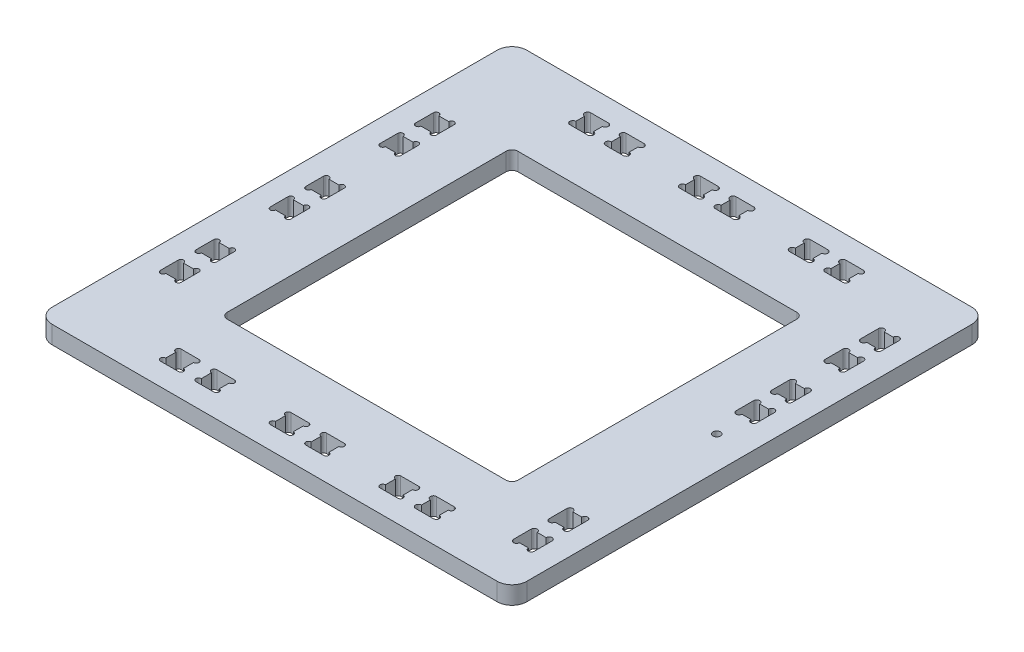
SolidWorks part; units mm, degrees
ref_plane "정면" through (0, 0, 0) normal (0, 0, 1) x (1, 0, 0)
ref_plane "윗면" through (0, 0, 0) normal (0, 1, 0) x (1, 0, 0)
ref_plane "우측면" through (0, 0, 0) normal (1, 0, 0) x (0, 0, -1)
sketch "스케치1" plane through (0, 0, 0) normal (0, 1, 0) x (1, 0, 0)
  line L1 (-80, -80) -> (80, -80)
  line L2 (-80, -80) -> (-80, 80)
  line L3 (-80, 80) -> (80, 80)
  line L4 (80, -80) -> (80, 80)
  line L5 (-80, -80) -> (80, 80) construction
  line L6 (-80, 80) -> (80, -80) construction
  line L7 (-49, -49) -> (49, -49)
  line L8 (-49, -49) -> (-49, 49)
  line L9 (-49, 49) -> (49, 49)
  line L10 (49, -49) -> (49, 49)
  line L11 (-49, -49) -> (49, 49) construction
  line L12 (-49, 49) -> (49, -49) construction
  point P0 (0, 0)
  point P6 (0, 0)
  dimension "D1" = 98
  dimension "D2" = 98
  dimension "D3" = 160
  dimension "D4" = 160
extrude "보스-돌출1" add sketch "스케치1" along normal blind 6
sketch "스케치2" plane through (0, 0, 0) normal (0, -1, 0) x (1, 0, 0)
  line L1 (-46, 72.5) -> (-40, 72.5)
  line L2 (-46, 72.5) -> (-46, 65.5)
  line L3 (-46, 65.5) -> (-40, 65.5)
  line L4 (-40, 72.5) -> (-40, 65.5)
  line L5 (-34, 72.5) -> (-28, 72.5)
  line L6 (-34, 72.5) -> (-34, 65.5)
  line L7 (-34, 65.5) -> (-28, 65.5)
  line L8 (-28, 72.5) -> (-28, 65.5)
  line L9 (-9, 72.5) -> (-3, 72.5)
  line L10 (-9, 72.5) -> (-9, 65.5)
  line L11 (-9, 65.5) -> (-3, 65.5)
  line L12 (-3, 72.5) -> (-3, 65.5)
  line L13 (3, 72.5) -> (9, 72.5)
  line L14 (3, 72.5) -> (3, 65.5)
  line L15 (3, 65.5) -> (9, 65.5)
  line L16 (9, 72.5) -> (9, 65.5)
  line L17 (28, 72.5) -> (34, 72.5)
  line L18 (28, 72.5) -> (28, 65.5)
  line L19 (28, 65.5) -> (34, 65.5)
  line L20 (34, 72.5) -> (34, 65.5)
  line L21 (40, 72.5) -> (46, 72.5)
  line L22 (40, 72.5) -> (40, 65.5)
  line L23 (40, 65.5) -> (46, 65.5)
  line L24 (46, 72.5) -> (46, 65.5)
  line L25 (65.5, 65) -> (72.5, 65)
  line L26 (65.5, 65) -> (65.5, 59)
  line L27 (65.5, 59) -> (72.5, 59)
  line L28 (72.5, 65) -> (72.5, 59)
  line L29 (65.5, 53) -> (72.5, 53)
  line L30 (65.5, 53) -> (65.5, 47)
  line L31 (65.5, 47) -> (72.5, 47)
  line L32 (72.5, 53) -> (72.5, 47)
  line L33 (65.5, -10) -> (72.5, -10)
  line L34 (65.5, -10) -> (65.5, -16)
  line L35 (65.5, -16) -> (72.5, -16)
  line L36 (72.5, -10) -> (72.5, -16)
  line L37 (65.5, -22) -> (72.5, -22)
  line L38 (65.5, -22) -> (65.5, -28)
  line L39 (65.5, -28) -> (72.5, -28)
  line L40 (72.5, -22) -> (72.5, -28)
  line L41 (65.5, -40) -> (72.5, -40)
  line L42 (65.5, -40) -> (65.5, -46)
  line L43 (65.5, -46) -> (72.5, -46)
  line L44 (72.5, -40) -> (72.5, -46)
  line L45 (65.5, -52) -> (72.5, -52)
  line L46 (65.5, -52) -> (65.5, -58)
  line L47 (65.5, -58) -> (72.5, -58)
  line L48 (72.5, -52) -> (72.5, -58)
  line L49 (3, -65.5) -> (9, -65.5)
  line L50 (3, -65.5) -> (3, -72.5)
  line L51 (3, -72.5) -> (9, -72.5)
  line L52 (9, -65.5) -> (9, -72.5)
  line L53 (-3, -65.5) -> (-9, -65.5)
  line L54 (-3, -65.5) -> (-3, -72.5)
  line L55 (-3, -72.5) -> (-9, -72.5)
  line L56 (-9, -65.5) -> (-9, -72.5)
  line L57 (-28, -65.5) -> (-34, -65.5)
  line L58 (-28, -65.5) -> (-28, -72.5)
  line L59 (-28, -72.5) -> (-34, -72.5)
  line L60 (-34, -65.5) -> (-34, -72.5)
  line L61 (-40, -65.5) -> (-46, -65.5)
  line L62 (-40, -65.5) -> (-40, -72.5)
  line L63 (-40, -72.5) -> (-46, -72.5)
  line L64 (-46, -65.5) -> (-46, -72.5)
  line L65 (-65.5, -40) -> (-72.5, -40)
  line L66 (-65.5, -40) -> (-65.5, -46)
  line L67 (-65.5, -46) -> (-72.5, -46)
  line L68 (-72.5, -40) -> (-72.5, -46)
  line L69 (-72.5, -34) -> (-65.5, -34)
  line L70 (-72.5, -34) -> (-72.5, -28)
  line L71 (-72.5, -28) -> (-65.5, -28)
  line L72 (-65.5, -34) -> (-65.5, -28)
  line L73 (-72.5, -9) -> (-65.5, -9)
  line L74 (-72.5, -9) -> (-72.5, -3)
  line L75 (-72.5, -3) -> (-65.5, -3)
  line L76 (-65.5, -9) -> (-65.5, -3)
  line L77 (-72.5, 3) -> (-65.5, 3)
  line L78 (-72.5, 3) -> (-72.5, 9)
  line L79 (-72.5, 9) -> (-65.5, 9)
  line L80 (-65.5, 3) -> (-65.5, 9)
  line L81 (-72.5, 28) -> (-65.5, 28)
  line L82 (-72.5, 28) -> (-72.5, 34)
  line L83 (-72.5, 34) -> (-65.5, 34)
  line L84 (-65.5, 28) -> (-65.5, 34)
  line L85 (-72.5, 40) -> (-65.5, 40)
  line L86 (-72.5, 40) -> (-72.5, 46)
  line L87 (-72.5, 46) -> (-65.5, 46)
  line L88 (-65.5, 40) -> (-65.5, 46)
  line L89 (28, -65.5) -> (34, -65.5)
  line L90 (28, -65.5) -> (28, -72.5)
  line L91 (28, -72.5) -> (34, -72.5)
  line L92 (34, -65.5) -> (34, -72.5)
  line L93 (40, -65.5) -> (46, -65.5)
  line L94 (40, -65.5) -> (40, -72.5)
  line L95 (40, -72.5) -> (46, -72.5)
  line L96 (46, -65.5) -> (46, -72.5)
extrude "컷-돌출1" cut sketch "스케치2" against normal blind 10
fillet "필렛1" radius 5 4 edges at (-80, 3, -80) (80, 3, -80) (80, 3, 80) (-80, 3, 80)
fillet "필렛2" radius 2 4 edges at (49, 3, 49) (49, 3, -49) (-49, 3, -49) (-49, 3, 49)
sketch "스케치3" plane through (0, 6, 0) normal (0, 1, 0) x (1, 0, 0)
  line L0 (80, 10) -> (73.6162, 3.6162)
  line L1 (80, -75) -> (80, 75) construction
  line L2 (73.6162, 3.6162) -> (73.6162, -35.3838)
  line L3 (73.6162, -35.3838) -> (80, -41.7676)
  line L4 (80, 10) -> (80, -41.7676)
  line L6 (72.5, 10) -> (80, 10) construction
  dimension "D1" = 45
  dimension "D2" = 45
  dimension "D3" = 39
extrude "컷-돌출2" [suppressed] cut sketch "스케치3" against normal blind 10
sketch "스케치4" plane through (0, 6, 0) normal (0, 1, 0) x (1, 0, 0)
  line L0 (49, 0) -> (84.68, 0) construction
  line L1 (49, -47) -> (49, 47) construction
  circle A0 centre (69, 0) radius 1.25
  dimension "D1" = 2.5
  dimension "D2" = 20
extrude "컷-돌출3" cut sketch "스케치4" against normal through all
sketch "스케치5" plane through (0, 6, 0) normal (0, 1, 0) x (1, 0, 0)
  line L0 (46, 72.5) -> (46, 65.5) construction
  line L1 (40, 65.5) -> (40, 72.5) construction
  line L2 (34, 72.5) -> (34, 65.5) construction
  line L3 (28, 65.5) -> (28, 72.5) construction
  line L4 (9, 72.5) -> (9, 65.5) construction
  line L5 (3, 65.5) -> (3, 72.5) construction
  line L6 (-3, 72.5) -> (-3, 65.5) construction
  line L7 (-9, 65.5) -> (-9, 72.5) construction
  line L8 (-40, 72.5) -> (-40, 65.5) construction
  line L9 (-46, 65.5) -> (-46, 72.5) construction
  line L10 (-34, 65.5) -> (-34, 72.5) construction
  line L11 (-28, 72.5) -> (-28, 65.5) construction
  line L12 (65.5, 58) -> (72.5, 58) construction
  line L13 (72.5, 52) -> (65.5, 52) construction
  line L14 (72.5, 40) -> (65.5, 40) construction
  line L15 (65.5, 46) -> (72.5, 46) construction
  line L16 (65.5, 28) -> (72.5, 28) construction
  line L17 (72.5, 22) -> (65.5, 22) construction
  line L18 (65.5, 16) -> (72.5, 16) construction
  line L19 (72.5, 10) -> (65.5, 10) construction
  line L20 (65.5, -47) -> (72.5, -47) construction
  line L21 (72.5, -53) -> (65.5, -53) construction
  line L22 (65.5, -59) -> (72.5, -59) construction
  line L23 (72.5, -65) -> (65.5, -65) construction
  line L24 (46, -65.5) -> (46, -72.5) construction
  line L25 (40, -72.5) -> (40, -65.5) construction
  line L26 (34, -65.5) -> (34, -72.5) construction
  line L27 (28, -72.5) -> (28, -65.5) construction
  line L28 (3, -72.5) -> (3, -65.5) construction
  line L29 (9, -65.5) -> (9, -72.5) construction
  line L30 (-3, -65.5) -> (-3, -72.5) construction
  line L31 (-9, -72.5) -> (-9, -65.5) construction
  line L32 (-34, -72.5) -> (-34, -65.5) construction
  line L33 (-28, -65.5) -> (-28, -72.5) construction
  line L34 (-40, -65.5) -> (-40, -72.5) construction
  line L35 (-46, -72.5) -> (-46, -65.5) construction
  line L36 (-72.5, 46) -> (-65.5, 46) construction
  line L37 (-65.5, 40) -> (-72.5, 40) construction
  line L38 (-72.5, 34) -> (-65.5, 34) construction
  line L39 (-65.5, 28) -> (-72.5, 28) construction
  line L40 (-72.5, 9) -> (-65.5, 9) construction
  line L41 (-65.5, 3) -> (-72.5, 3) construction
  line L42 (-72.5, -3) -> (-65.5, -3) construction
  line L43 (-65.5, -9) -> (-72.5, -9) construction
  line L44 (-72.5, -28) -> (-65.5, -28) construction
  line L45 (-65.5, -34) -> (-72.5, -34) construction
  line L46 (-72.5, -40) -> (-65.5, -40) construction
  line L47 (-65.5, -46) -> (-72.5, -46) construction
  circle A0 centre (28, -66.4077) radius 0.9077
  circle A1 centre (40, 71.5) radius 1
  circle A2 centre (40, 66.5) radius 1
  circle A3 centre (46, 66.5) radius 1
  circle A4 centre (34, 71.5) radius 1
  circle A5 centre (28, 71.5) radius 1
  circle A6 centre (28, 66.5) radius 1
  circle A7 centre (34, 66.5) radius 1
  circle A8 centre (9, 71.5) radius 1
  circle A9 centre (3, 71.5) radius 1
  circle A10 centre (3, 66.5) radius 1
  circle A11 centre (9, 66.5) radius 1
  circle A12 centre (-3, 71.5) radius 1
  circle A13 centre (-3, 66.5) radius 1
  circle A14 centre (-9, 66.5) radius 1
  circle A15 centre (-9, 71.5) radius 1
  circle A16 centre (-40, 71.5) radius 1
  circle A17 centre (-40, 66.5) radius 1
  circle A18 centre (-46, 66.5) radius 1
  circle A19 centre (-46, 71.5) radius 1
  circle A20 centre (-34, 71.5) radius 1
  circle A21 centre (-28, 71.5) radius 1
  circle A22 centre (-28, 66.5) radius 1
  circle A23 centre (-34, 66.5) radius 1
  circle A24 centre (71.5, 58) radius 1
  circle A25 centre (66.5, 58) radius 1
  circle A26 centre (66.5, 52) radius 1
  circle A27 centre (71.5, 52) radius 1
  circle A28 centre (66.5, 40) radius 1
  circle A29 centre (66.5, 46) radius 1
  circle A30 centre (71.5, 46) radius 1
  circle A31 centre (71.5, 40) radius 1
  circle A32 centre (66.5, 28) radius 1
  circle A33 centre (71.5, 28) radius 1
  circle A34 centre (71.5, 22) radius 1
  circle A35 centre (66.5, 22) radius 1
  circle A36 centre (66.5, 16) radius 1
  circle A37 centre (71.5, 16) radius 1
  circle A38 centre (71.5, 10) radius 1
  circle A39 centre (66.5, 10) radius 1
  circle A40 centre (66.5, -47) radius 1
  circle A41 centre (66.5, -53) radius 1
  circle A42 centre (71.5, -53) radius 1
  circle A43 centre (71.5, -47) radius 1
  circle A44 centre (71.5, -59) radius 1
  circle A45 centre (66.5, -59) radius 1
  circle A46 centre (66.5, -65) radius 1
  circle A47 centre (71.5, -65) radius 1
  circle A48 centre (46, -66.5) radius 1
  circle A49 centre (40, -66.5) radius 1
  circle A50 centre (40, -71.5) radius 1
  circle A51 centre (46, -71.5) radius 1
  circle A52 centre (34, -66.5) radius 1
  circle A53 centre (46, 71.5923) radius 0.9077
  circle A54 centre (28, -71.5923) radius 0.9077
  circle A55 centre (34, -71.5923) radius 0.9077
  circle A56 centre (3, -66.4077) radius 0.9077
  circle A57 centre (9, -66.4077) radius 0.9077
  circle A58 centre (9, -71.5923) radius 0.9077
  circle A59 centre (3, -71.5923) radius 0.9077
  circle A60 centre (-3, -66.4077) radius 0.9077
  circle A61 centre (-3, -71.5923) radius 0.9077
  circle A62 centre (-9, -66.4077) radius 0.9077
  circle A63 centre (-9, -71.5923) radius 0.9077
  circle A64 centre (-34, -66.4077) radius 0.9077
  circle A65 centre (-28, -66.4077) radius 0.9077
  circle A66 centre (-28, -71.5923) radius 0.9077
  circle A67 centre (-34, -71.5923) radius 0.9077
  circle A68 centre (-40, -66.4077) radius 0.9077
  circle A69 centre (-46, -66.4077) radius 0.9077
  circle A70 centre (-46, -71.5923) radius 0.9077
  circle A71 centre (-40, -71.5923) radius 0.9077
  circle A72 centre (-66.4077, 46) radius 0.9077
  circle A73 centre (-71.5923, 46) radius 0.9077
  circle A74 centre (-71.5923, 40) radius 0.9077
  circle A75 centre (-66.4077, 40) radius 0.9077
  circle A76 centre (-66.4077, 34) radius 0.9077
  circle A77 centre (-71.5923, 34) radius 0.9077
  circle A78 centre (-66.4077, 28) radius 0.9077
  circle A79 centre (-71.5923, 28) radius 0.9077
  circle A80 centre (-66.4077, 9) radius 0.9077
  circle A81 centre (-71.5923, 9) radius 0.9077
  circle A82 centre (-71.5923, 3) radius 0.9077
  circle A83 centre (-66.4077, 3) radius 0.9077
  circle A84 centre (-66.4077, -3) radius 0.9077
  circle A85 centre (-71.5923, -3) radius 0.9077
  circle A86 centre (-66.4077, -9) radius 0.9077
  circle A87 centre (-71.5923, -9) radius 0.9077
  circle A88 centre (-66.4077, -28) radius 0.9077
  circle A89 centre (-71.5923, -28) radius 0.9077
  circle A90 centre (-71.5923, -34) radius 0.9077
  circle A91 centre (-66.4077, -34) radius 0.9077
  circle A92 centre (-66.4077, -40) radius 0.9077
  circle A93 centre (-71.5923, -40) radius 0.9077
  circle A94 centre (-71.5923, -46) radius 0.9077
  circle A95 centre (-66.4077, -46) radius 0.9077
  dimension "D1" = 2
extrude "컷-돌출4" cut sketch "스케치5" against normal blind 10
